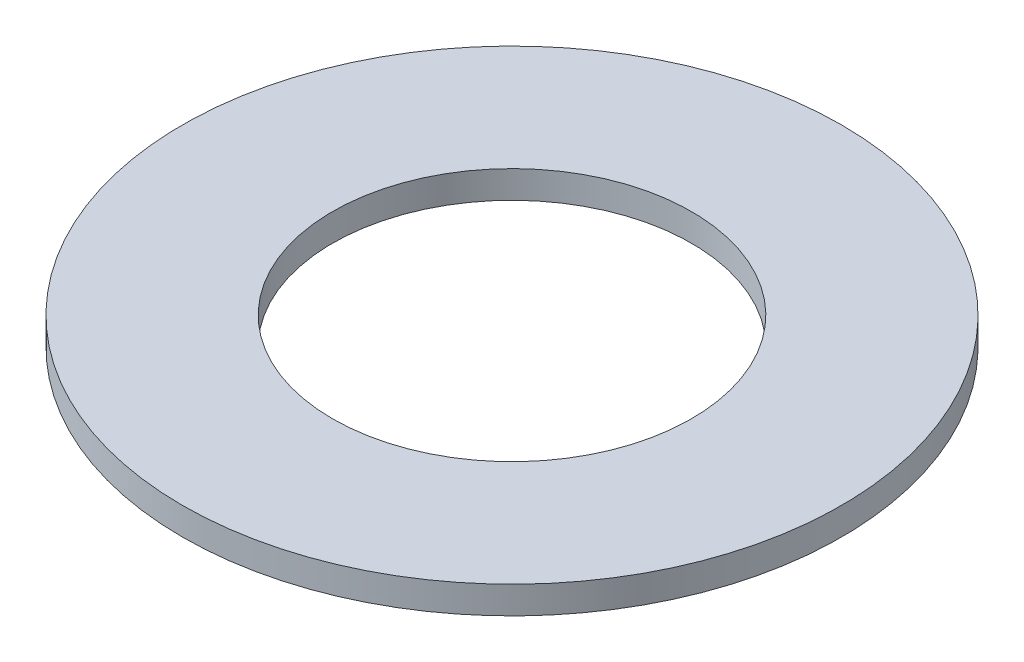
SolidWorks part; units mm, degrees
ref_plane "Front Plane" through (0, 0, 0) normal (0, 0, 1) x (1, 0, 0)
ref_plane "Top Plane" through (0, 0, 0) normal (0, 1, 0) x (1, 0, 0)
ref_plane "Right Plane" through (0, 0, 0) normal (1, 0, 0) x (0, 0, -1)
sketch "Sketch1" plane through (0, 0, 0) normal (0, 1, 0) x (1, 0, 0)
  circle A0 centre (0, 0) radius 38.1
  circle A1 centre (0, 0) radius 20.7518
  dimension "D1" = 76.2
  dimension "D2" = 41.5036
extrude "Boss-Extrude1" add sketch "Sketch1" along normal blind 3.175
